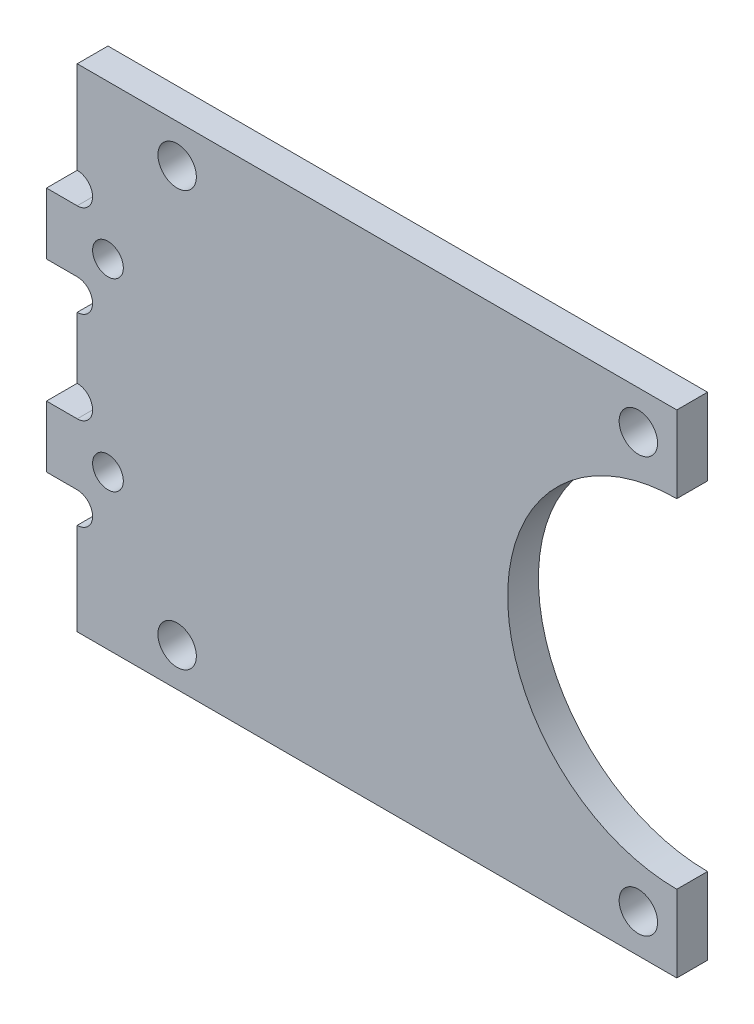
SolidWorks part; units mm, degrees
material "自訂玻璃纖維"
ref_plane "前基準面" through (0, 0, 0) normal (0, 0, 1) x (1, 0, 0)
ref_plane "上基準面" through (0, 0, 0) normal (0, 1, 0) x (1, 0, 0)
ref_plane "右基準面" through (0, 0, 0) normal (1, 0, 0) x (0, 0, -1)
sketch "草圖1" plane through (0, 0, 0) normal (0, 0, 1) x (1, 0, 0)
  line L0 (-17.2162, 10.1625) -> (13.2838, 10.1625)
  line L1 (13.2838, 10.1625) -> (13.2838, -21.8375)
  line L2 (13.2838, -21.8375) -> (-17.2162, -21.8375)
  line L3 (-25.7162, 2.1625) -> (-27.7162, 2.1625)
  line L4 (-27.7162, 2.1625) -> (-27.7162, -1.8375)
  line L5 (-17.2162, 10.1625) -> (-21.7162, 10.1625)
  line L6 (-27.7162, -1.8375) -> (-25.7162, -1.8375)
  line L7 (-17.2162, -21.8375) -> (-19.7162, -21.8375)
  line L8 (-25.7162, -3.8375) -> (-25.7162, -7.8375)
  line L9 (-21.7162, 10.1625) -> (-25.7162, 10.1625)
  line L10 (-25.7162, -9.8375) -> (-27.7162, -9.8375)
  line L11 (-19.7162, -21.8375) -> (-25.7162, -21.8375)
  line L12 (-25.7162, 10.1625) -> (-25.7162, 4.1625)
  line L13 (-27.7162, -9.8375) -> (-27.7162, -13.8375)
  line L14 (-27.7162, -13.8375) -> (-25.7162, -13.8375)
  line L16 (-25.7162, -15.8375) -> (-25.7162, -21.8375)
  circle A0 centre (-19.2162, 7.6625) radius 1.25
  circle A1 centre (-19.2162, -19.3375) radius 1.25
  circle A2 centre (10.7838, -19.3375) radius 1.25
  circle A3 centre (10.7838, 7.6625) radius 1.25
  circle A4 centre (-23.7162, -11.8375) radius 1
  circle A5 centre (-23.7162, 0.1625) radius 1
  arc A6 (-25.7162, 2.1625) -> (-25.7162, 4.1625) centre (-25.7162, 3.1625) ccw
  arc A7 (-25.7162, -1.8375) -> (-25.7162, -3.8375) centre (-25.7162, -2.8375) cw
  arc A8 (-25.7162, -9.8375) -> (-25.7162, -7.8375) centre (-25.7162, -8.8375) ccw
  arc A9 (-25.7162, -13.8375) -> (-25.7162, -15.8375) centre (-25.7162, -14.8375) cw
  dimension "D7" = 12
  dimension "D8" = 30
  dimension "D9" = 6.5
  dimension "D12" = 2
  dimension "D4" = 2.5
  dimension "D5" = 30
  dimension "D6" = 4
  dimension "D2" = 2.5
  dimension "D3" = 35
extrude "填料-伸長1" add sketch "草圖1" along normal blind 2
sketch "草圖4" plane through (0, 0, 0) normal (0, 0, -1) x (-1, 0, 0)
  line L1 (-13.2838, -21.8375) -> (-13.2838, 10.1625) construction
  line L4 (-13.2838, -16.8375) -> (-13.2838, 5.1625)
  arc A2 (-13.2838, 5.1625) -> (-13.2838, -16.8375) centre (-13.2838, -5.8375) cw
extrude "除料-伸長1" cut sketch "草圖4" against normal blind 2
